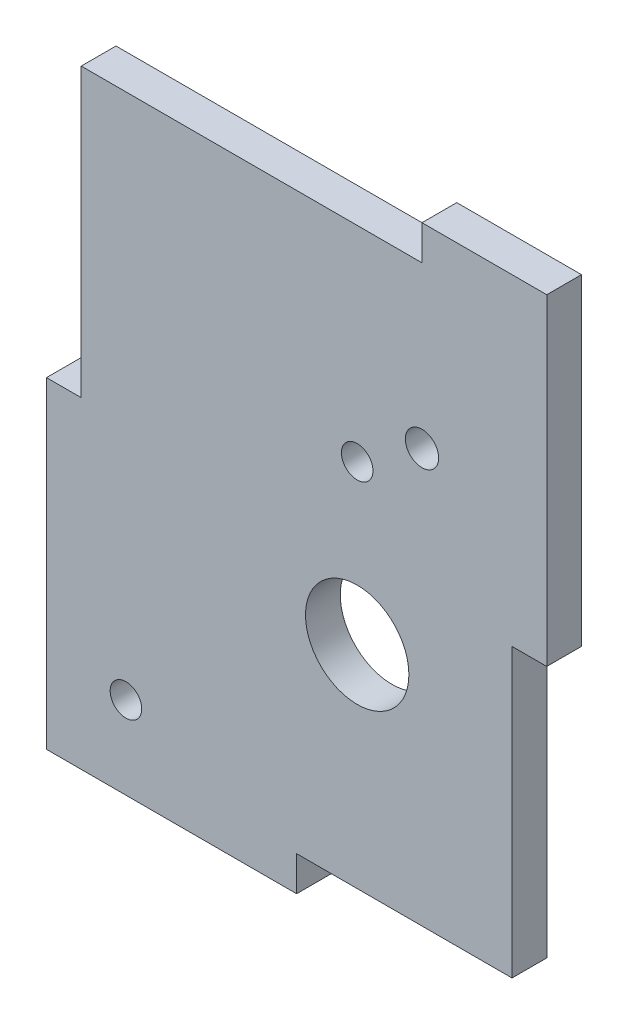
SolidWorks part; units mm, degrees
ref_plane "Front Plane" through (0, 0, 0) normal (0, 0, 1) x (1, 0, 0)
ref_plane "Top Plane" through (0, 0, 0) normal (0, 1, 0) x (1, 0, 0)
ref_plane "Right Plane" through (0, 0, 0) normal (1, 0, 0) x (0, 0, -1)
sketch "backSketch" plane through (0, 0, 0) normal (0, 0, 1) x (1, 0, 0)
  line L0 (14.1799, 18.4623) -> (24.4068, 18.6777) construction
  line L1 (0, 0) -> (38.1, 0)
  line L2 (0, 0) -> (0, 50.8)
  line L3 (0, 50.8) -> (38.1, 50.8)
  line L4 (38.1, 0) -> (38.1, 50.8)
  line L5 (3.953, 4.2295) -> (24.4068, 32.695) construction
  line L6 (24.4068, 18.6777) -> (30.1383, 36.5785) construction
  line L9 (30.1383, 50.8) -> (30.1383, 53.8734)
  line L10 (30.1383, 36.5785) -> (30.1383, 50.8) construction
  line L12 (30.1383, 53.8734) -> (41.1734, 53.8734)
  line L13 (41.1734, 53.8734) -> (41.1734, 25.4)
  line L14 (41.1734, 25.4) -> (38.1, 25.4)
  line L15 (0, 25.4) -> (-3.0734, 25.4)
  line L16 (-3.0734, 25.4) -> (-3.0734, -3.0734)
  line L17 (-3.0734, -3.0734) -> (19.05, -3.0734)
  line L18 (19.05, -3.0734) -> (19.05, 0)
  circle A0 centre (3.953, 4.2295) radius 1.397
  circle A1 centre (24.4068, 32.695) radius 1.397
  circle A3 centre (24.4068, 18.6777) radius 4.572
  circle A4 centre (30.1383, 36.5785) radius 1.4732
  point P10 (14.1799, 18.4623)
  point P13 (0, 0)
  dimension "D2" = 3.0734
  dimension "D3" = 3.0734
  dimension "holeDia" = 2.794
  dimension "D4" = 3.0734
  dimension "motorAxleDia" = 9.144
  dimension "D1" = 3.0734
  dimension "nailAxleDia" = 2.9464
  dimension "width" = 38.1
  dimension "height" = 50.8
  dimension "MtoG" = 18.796
  dimension "hole2hole" = 35.052
  dimension "y2" = 14.2215
  dimension "MtoBottom" = 18.6777
extrude "Boss-Extrude1" add sketch "backSketch" along normal blind 3.0734 contours L14 L13 L12 L9 L3 L4 | L17 L18 L1 L2 L15 L16 | L1 L4 L3 L2 A4 A3 A1 A0
